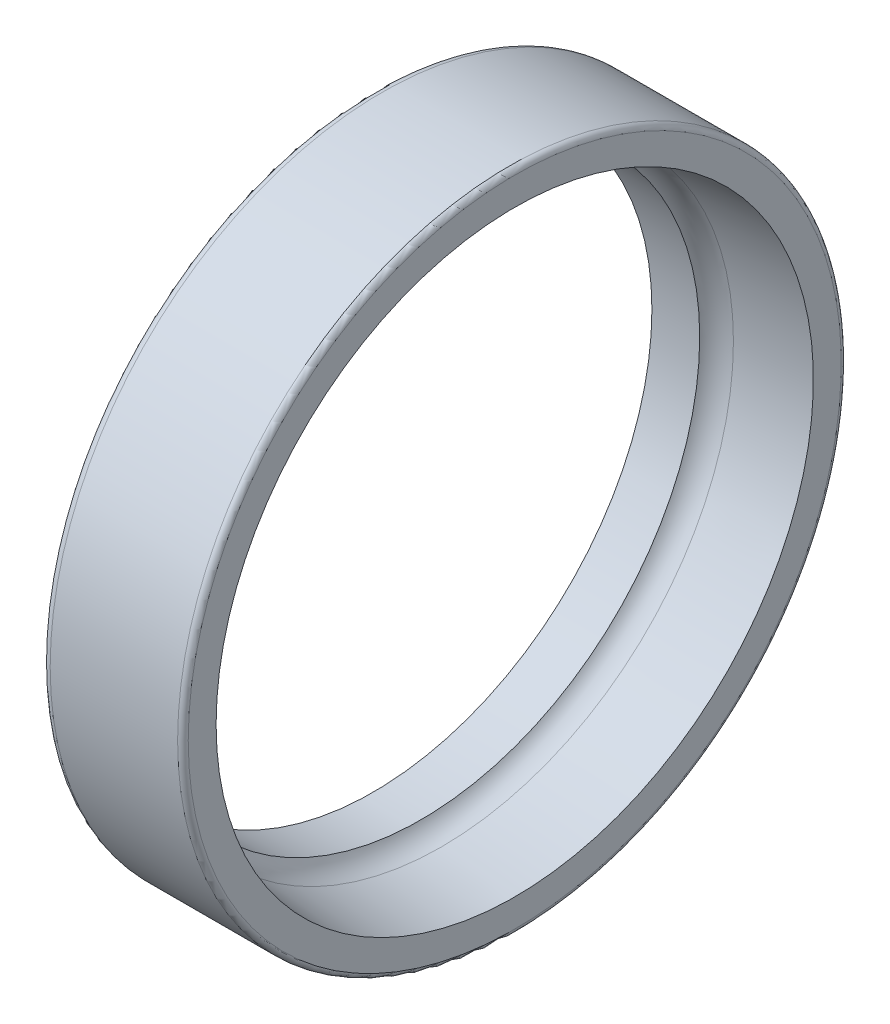
SolidWorks part; units mm, degrees
ref_plane "Front Plane" through (0, 0, 0) normal (0, 0, 1) x (1, 0, 0)
ref_plane "Top Plane" through (0, 0, 0) normal (0, 1, 0) x (1, 0, 0)
ref_plane "Right Plane" through (0, 0, 0) normal (1, 0, 0) x (0, 0, -1)
ref_plane "Plane1" through (0, 0, 0) normal (0, 0, 1) x (1, 0, 0)
sketch "Sketch1" plane through (0, 0, 0) normal (0, 0, 1) x (1, 0, 0)
  line L0 (0, 31.5) -> (5.4019, 31.5)
  line L1 (7.7247, 32.9873) -> (16, 33.75)
  line L2 (16, 33.75) -> (16, 36.9)
  line L3 (15.4, 37.5) -> (1, 37.5)
  line L4 (0, 36.5) -> (0, 31.5)
  line L5 (16, 0) -> (0, 0) construction
  arc A0 (5.4019, 31.5) -> (7.7247, 32.9873) centre (8, 30) cw
  arc A1 (16, 36.9) -> (15.4, 37.5) centre (15.4, 36.9) ccw
  arc A2 (1, 37.5) -> (0, 36.5) centre (1, 36.5) ccw
revolve "Revolve1" add sketch "Sketch1" angle 360 about L5
